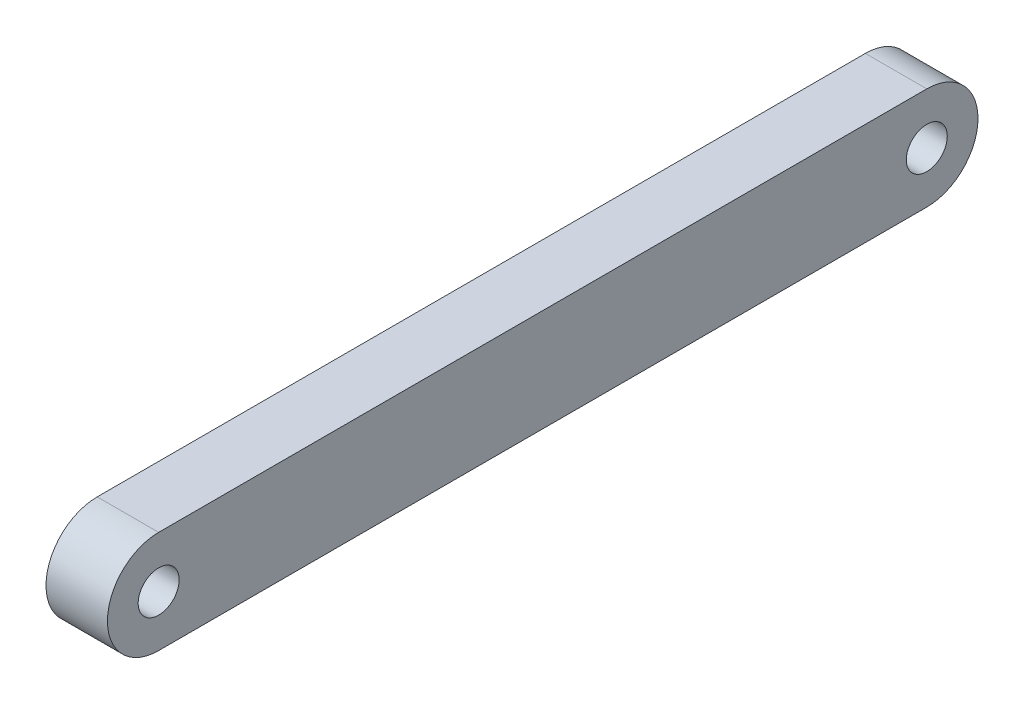
SolidWorks part; units mm, degrees
ref_plane "前视基准面" through (0, 0, 0) normal (0, 0, 1) x (1, 0, 0)
ref_plane "上视基准面" through (0, 0, 0) normal (0, 1, 0) x (1, 0, 0)
ref_plane "右视基准面" through (0, 0, 0) normal (1, 0, 0) x (0, 0, -1)
other "Configuration Table"
sketch "草图1" plane through (0, 0, 0) normal (1, 0, 0) x (0, 0, -1)
  line L0 (0, 0) -> (75, 0) construction
  line L1 (0, 5) -> (75, 5)
  line L2 (0, -5) -> (75, -5)
  arc A0 (0, 5) -> (0, -5) centre (0, 0) ccw
  arc A1 (75, -5) -> (75, 5) centre (75, 0) ccw
  point P3 (37.5, 0)
  dimension "D1" = 75
  dimension "D2" = 10
extrude "凸台-拉伸1" add sketch "草图1" along normal blind 6
sketch "草图2" plane through (6, 0, 0) normal (1, 0, 0) x (0, 0, -1)
  circle A0 centre (75, 0) radius 2
  circle A1 centre (0, 0) radius 2
  dimension "D1" = 4
  dimension "D2" = 4
extrude "切除-拉伸1" cut sketch "草图2" against normal through all
